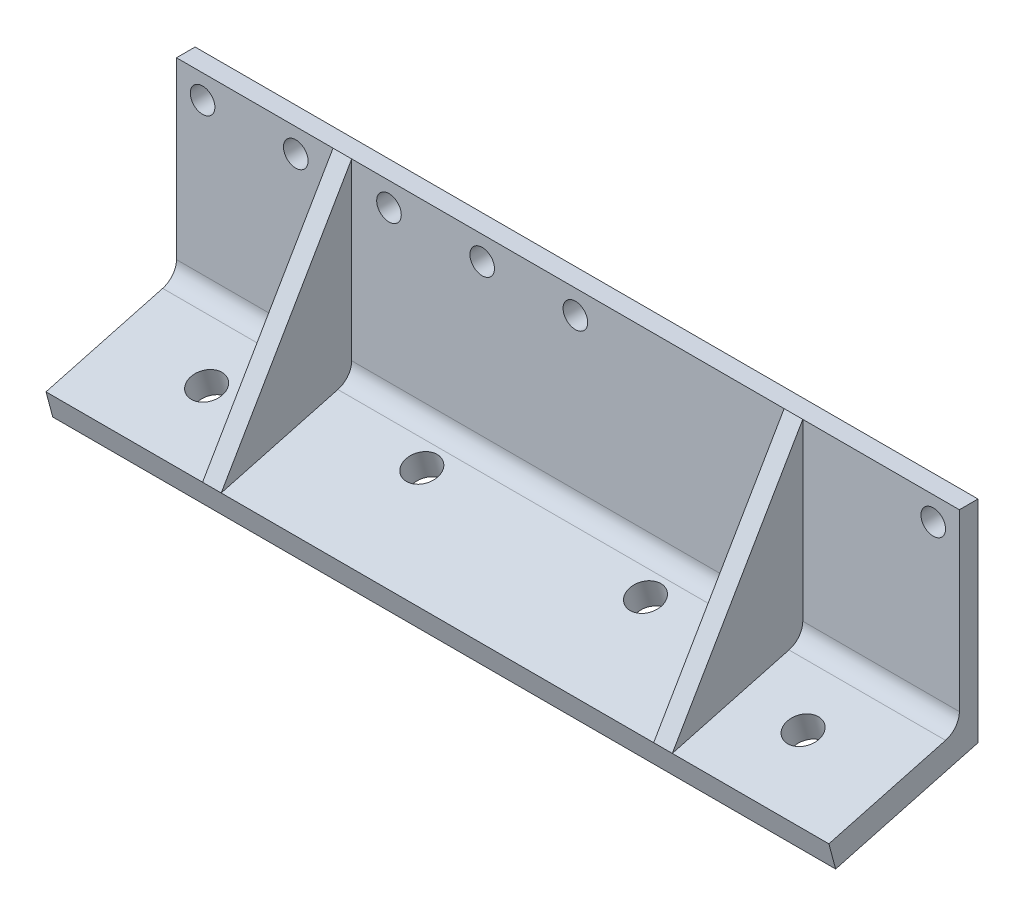
SolidWorks part; units mm, degrees
material "1060 合金"
ref_plane "前视基准面" through (0, 0, 0) normal (0, 0, 1) x (1, 0, 0)
ref_plane "上视基准面" through (0, 0, 0) normal (0, 1, 0) x (1, 0, 0)
ref_plane "右视基准面" through (0, 0, 0) normal (1, 0, 0) x (0, 0, -1)
sketch "草图1" plane through (0, 0, 0) normal (0, 1, 0) x (1, 0, 0)
  line L0 (0, 0) -> (170, 0) construction
  line L1 (170, 31.93) -> (170, -31.93)
  line L2 (15.8391, 73.3084) -> (162.1119, 41.7045)
  line L3 (15.8391, -73.3084) -> (162.1119, -41.7045)
  arc A0 (15.8391, 73.3084) -> (15.8391, -73.3084) centre (0, 0) ccw
  arc A1 (162.1119, -41.7045) -> (170, -31.93) centre (160, -31.93) ccw
  arc A2 (170, 31.93) -> (162.1119, 41.7045) centre (160, 31.93) ccw
  point P6 (170, 0)
  dimension "D1" = 150
  dimension "D4" = 20
  dimension "D5" = 20
  dimension "D2" = 170
  dimension "D3" = 63.86
extrude "凸台-拉伸1" add sketch "草图1" along normal blind 30
sketch "草图2" plane through (0, 30, 0) normal (0, 1, 0) x (1, 0, 0)
  circle A0 centre (0, 0) radius 44.45
  dimension "D1" = 88.9
extrude "切除-拉伸1" cut sketch "草图2" against normal blind 4
sketch "草图3" plane through (0, 26, 0) normal (0, 1, 0) x (1, 0, 0)
  line L0 (0, 0) -> (0, 90.3276) construction
  circle A0 centre (0, 0) radius 25.5
  circle A1 centre (0, 41) radius 2.25
  circle A2 centre (28.9914, 28.9914) radius 2.25
  circle A3 centre (41, 0) radius 2.25
  circle A4 centre (28.9914, -28.9914) radius 2.25
  circle A5 centre (0, -41) radius 2.25
  circle A6 centre (-28.9914, -28.9914) radius 2.25
  circle A7 centre (-41, 0) radius 2.25
  circle A8 centre (-28.9914, 28.9914) radius 2.25
  dimension "D1" = 51
  dimension "D3" = 4.5
  dimension "D2" = 41
  dimension "D4" = 8
extrude "切除-拉伸2" cut sketch "草图3" against normal through all contours A2 | A3 | A4 | A5 | A6 | A7 | A8 | A1 | A0
sketch "草图4" plane through (0, 30, 0) normal (0, 1, 0) x (1, 0, 0)
  line L0 (0, 0) -> (134, 0) construction
  line L1 (124, 18.5) -> (134, 18.5)
  line L2 (124, -18.5) -> (134, -18.5)
  arc A0 (134, -18.5) -> (134, 18.5) centre (134, 0) ccw
  arc A1 (124, 18.5) -> (124, -18.5) centre (124, 0) ccw
  dimension "D2" = 37
  dimension "D3" = 37
  dimension "D1" = 134
  dimension "D4" = 10
extrude "切除-拉伸3" cut sketch "草图4" against normal through all
sketch "草图5" plane through (0, 30, 0) normal (0, 1, 0) x (1, 0, 0)
  arc A0 (134, -18.5) -> (134, 18.5) centre (134, 0) ccw construction
  arc A1 (124, 18.5) -> (124, -18.5) centre (124, 0) ccw construction
  arc A2 (134, -18.5) -> (134, 18.5) centre (134, 0) ccw construction
  arc A3 (124, 18.5) -> (124, -18.5) centre (124, 0) ccw construction
  circle A4 centre (116.75, 25.5) radius 1.65
  circle A5 centre (141.25, 25.5) radius 1.65
  circle A6 centre (141.25, -25.5) radius 1.65
  circle A7 centre (116.75, -25.5) radius 1.65
  dimension "D1" = 3.3
  dimension "D2" = 3.3
  dimension "D3" = 3.3
  dimension "D4" = 3.3
  dimension "D7" = 25.5
  dimension "D5" = 7.25
  dimension "D6" = 25.5
  dimension "D8" = 7.25
  dimension "D9" = 7.25
extrude "切除-拉伸4" cut sketch "草图5" against normal through all
sketch "草图6" plane through (0, 30, 0) normal (0, 1, 0) x (1, 0, 0)
  line L0 (158, 42.5929) -> (158, -42.5929) construction
  line L2 (-52, 54.0463) -> (-52, -54.0463) construction
  line L6 (162.1119, 41.7045) -> (15.8391, 73.3084) construction
  line L7 (15.8391, -73.3084) -> (162.1119, -41.7045) construction
  line L8 (-52, 95) -> (-52, -95)
  line L9 (158, 95) -> (158, -95)
  line L10 (-52, 95) -> (158, 95)
  line L11 (-52, -95) -> (158, -95)
  line L15 (162.1119, 41.7045) -> (15.8391, 73.3084)
  line L16 (15.8391, -73.3084) -> (162.1119, -41.7045)
  line L17 (170, -31.93) -> (170, 31.93)
  line L18 (162.1119, 41.7045) -> (15.8391, 73.3084)
  line L19 (15.8391, -73.3084) -> (162.1119, -41.7045)
  line L20 (170, -31.93) -> (170, 31.93)
  arc A0 (15.8391, 73.3084) -> (15.8391, -73.3084) centre (0, 0) ccw construction
  arc A6 (170, 31.93) -> (162.1119, 41.7045) centre (160, 31.93) ccw
  arc A7 (15.8391, 73.3084) -> (15.8391, -73.3084) centre (0, 0) ccw
  arc A8 (162.1119, -41.7045) -> (170, -31.93) centre (160, -31.93) ccw
  arc A9 (170, 31.93) -> (162.1119, 41.7045) centre (160, 31.93) ccw
  arc A10 (15.8391, 73.3084) -> (15.8391, -73.3084) centre (0, 0) ccw
  arc A11 (162.1119, -41.7045) -> (170, -31.93) centre (160, -31.93) ccw
  point P8 (-52, 0)
  point P13 (158, 0)
  line M26 (162.1119, 41.7045) -> (15.8391, 73.3084)
  arc M27 (15.8391, 73.3084) -> (15.8391, -73.3084) centre (0, 0) ccw
  line M28 (15.8391, -73.3084) -> (162.1119, -41.7045)
  dimension "D3" = 190
  dimension "D1" = 210
  dimension "D2" = 52
  dimension "D4" = 190
  dimension "D5" = 0
extrude "凸台-拉伸2" add sketch "草图6" against normal blind 30 contours L10 L8 L9 M27 M26 | L8 L11 L9 M28 M27
sketch "草图7" plane through (0, 30, 0) normal (0, 1, 0) x (1, 0, 0)
  line L0 (-52, 54.0463) -> (-52, -54.0463)
  line L1 (158, 42.5929) -> (158, -42.5929)
  line L9 (162.1119, 41.7045) -> (158, 42.5929)
  line L10 (158, 42.5929) -> (158, 95)
  line L11 (158, 95) -> (-52, 95)
  line L12 (-52, 95) -> (-52, 54.0463)
  line L13 (-52, -54.0463) -> (-52, -95)
  line L14 (-52, -95) -> (158, -95)
  line L15 (158, -95) -> (158, -42.5929)
  line L16 (158, -42.5929) -> (162.1119, -41.7045)
  line L17 (170, -31.93) -> (170, 31.93)
  line L18 (162.1119, 41.7045) -> (158, 42.5929)
  line L21 (-52, 95) -> (-52, 54.0463)
  line L25 (158, -42.5929) -> (162.1119, -41.7045)
  line L26 (170, -31.93) -> (170, 31.93)
  arc A3 (170, 31.93) -> (162.1119, 41.7045) centre (160, 31.93) ccw
  arc A4 (-52, 54.0463) -> (-52, -54.0463) centre (0, 0) ccw
  arc A5 (162.1119, -41.7045) -> (170, -31.93) centre (160, -31.93) ccw
  arc A6 (170, 31.93) -> (162.1119, 41.7045) centre (160, 31.93) ccw
  arc A7 (-52, 54.0463) -> (-52, -54.0463) centre (0, 0) ccw
  arc A8 (162.1119, -41.7045) -> (170, -31.93) centre (160, -31.93) ccw
  arc M22 (170, 31.93) -> (162.1119, 41.7045) centre (160, 31.93) ccw
  line M23 (162.1119, 41.7045) -> (158, 42.5929)
  arc M27 (-52, 54.0463) -> (-52, -54.0463) centre (0, 0) ccw
  line M31 (158, -42.5929) -> (162.1119, -41.7045)
  arc M32 (162.1119, -41.7045) -> (170, -31.93) centre (160, -31.93) ccw
  line M33 (170, -31.93) -> (170, 31.93)
  dimension "D1" = 0
extrude "切除-拉伸5" cut sketch "草图7" against normal through all contours L0 M27 | L1 M23 M31 M32 M33 M22
sketch "草图9" plane through (-52, 0, 0) normal (-1, 0, 0) x (0, 0, 1)
  line L0 (-95, 20) -> (-60, 10.6218)
  line L1 (-95, 30) -> (95, 30) construction
  line L3 (-60, 10.6218) -> (-60, 30)
  line L5 (-95, 0) -> (-95, 30) construction
  line L7 (-95, 20) -> (-95, 30)
  line L8 (-95, 30) -> (-60, 30)
  dimension "D1" = 15
  dimension "D3" = 19.3782
  dimension "D4" = 35
  dimension "D5" = 10
extrude "切除-拉伸7" cut sketch "草图9" against normal through all contours L8 L3 L0 L7
sketch "草图8" plane through (-52, 0, 0) normal (-1, 0, 0) x (0, 0, 1)
  line L0 (0, 0) -> (52, 0)
  line L1 (-95, 0) -> (95, 0) construction
  line L2 (52, 0) -> (52, 17.3)
  line L3 (52, 17.3) -> (-52, 17.3)
  line L4 (-52, 17.3) -> (-52, 0)
  line L5 (-52, 0) -> (0, 0)
  line L6 (-60, 30) -> (95, 30) construction
  dimension "D1" = 52
  dimension "D2" = 52
  dimension "D3" = 12.7
sketch "草图10" plane through (-52, 0, 0) normal (-1, 0, 0) x (0, 0, 1)
  line L0 (-95, 12.7531) -> (-47.4049, 0) construction
  line L1 (-95, 0) -> (-95, 20) construction
  line L2 (-95, 0) -> (95, 0) construction
  line L3 (-95, 20) -> (-60, 10.6218) construction
  line L6 (-95, 12.7531) -> (-52, 1.2313)
  line L7 (-52, 1.2313) -> (-52, 0)
  line L8 (-95, 12.7531) -> (-95, 0)
  line L9 (-95, 0) -> (-52, 0)
  line L10 (-52, 17.3) -> (-52, 0) construction
  dimension "D1" = 7
extrude "切除-拉伸8" cut sketch "草图10" against normal through all
extrude "切除-拉伸9" cut sketch "草图8" against normal through all
fillet "圆角1" radius 5 1 edges at (53, 10.6218, -60)
sketch "草图11" plane through (-52, 0, 0) normal (-1, 0, 0) x (0, 0, 1)
  line L0 (-95, 12.7531) -> (-93.1883, 19.5145)
  line L1 (-95, 20) -> (-66.2941, 12.3083) construction
  line L2 (-93.1883, 19.5145) -> (-95, 20)
  line L3 (-95, 20) -> (-95, 12.7531)
extrude "切除-拉伸10" cut sketch "草图11" against normal through all
sketch "草图12" plane through (-52, 0, 0) normal (-1, 0, 0) x (0, 0, 1)
  line L0 (-93.1883, 19.5145) -> (-60, 30)
  line L10 (-93.1883, 19.5145) -> (-95, 12.7531)
  line L11 (-95, 12.7531) -> (-52, 1.2313)
  line L12 (-52, 1.2313) -> (-52, 17.3)
  line L13 (-52, 17.3) -> (52, 17.3)
  line L14 (52, 17.3) -> (52, 0)
  line L15 (52, 0) -> (95, 0)
  line L16 (95, 0) -> (95, 30)
  line L17 (95, 30) -> (-60, 30)
  line L18 (-60, 30) -> (-60, 17.1379)
  line L19 (-66.2941, 12.3083) -> (-93.1883, 19.5145)
  line L28 (-60, 30) -> (-60, 17.1379)
  line L29 (-66.2941, 12.3083) -> (-93.1883, 19.5145)
  arc A1 (-66.2941, 12.3083) -> (-60, 17.1379) centre (-65, 17.1379) ccw
  arc A2 (-66.2941, 12.3083) -> (-60, 17.1379) centre (-65, 17.1379) ccw
  dimension "D1" = 0
extrude "凸台-拉伸3" add sketch "草图12" against normal blind 5
sketch "草图13" plane through (158, 0, 0) normal (1, 0, 0) x (0, 0, -1)
  line L3 (66.2941, 12.3083) -> (93.1883, 19.5145)
  line L4 (93.1883, 19.5145) -> (60, 30)
  line L5 (60, 30) -> (60, 17.1379)
  line L6 (66.2941, 12.3083) -> (93.1883, 19.5145)
  line L7 (93.1883, 19.5145) -> (60, 30)
  line L8 (60, 30) -> (60, 17.1379)
  arc A1 (60, 17.1379) -> (66.2941, 12.3083) centre (65, 17.1379) ccw
  arc A2 (60, 17.1379) -> (66.2941, 12.3083) centre (65, 17.1379) ccw
  dimension "D1" = 0
extrude "凸台-拉伸4" add sketch "草图13" against normal blind 5
sketch "草图14" plane through (0, -5.0897, -1.3638) normal (0, 0.9659, 0.2588) x (1, 0, 0)
  line L0 (153, 67.2208) -> (153, 95.0637) construction
  line L3 (153, 95.0637) -> (-47, 95.0637) construction
  circle A0 centre (-27, 82.0637) radius 4.25
  circle A1 centre (23, 82.0637) radius 4.25
  circle A2 centre (83, 82.0637) radius 4.25
  circle A3 centre (133, 82.0637) radius 4.25
  dimension "D1" = 8.5
  dimension "D2" = 160
  dimension "D3" = 20
  dimension "D4" = 50
  dimension "D5" = 50
  dimension "D6" = 13
extrude "切除-拉伸11" cut sketch "草图14" against normal through all
sketch "草图16" plane through (-52, 0, 0) normal (-1, 0, 0) x (0, 0, 1)
  line L0 (-60, 30) -> (95, 30) construction
  line L1 (95, 0) -> (52, 0)
  line L2 (95, 0) -> (95, 30)
  line L3 (95, 30) -> (52, 30)
  line L4 (52, 0) -> (52, 30)
extrude "切除-拉伸12" cut sketch "草图16" against normal through all
ref_plane "基准面1" through (0, -11.8512, -3.1755) normal (0, -0.9659, -0.2588) x (-1, 0, 0)
sketch "草图18" plane through (0, 30, 0) normal (0, 1, 0) x (1, 0, 0)
  line L1 (-52, -52) -> (158, -52)
  line L2 (-52, -52) -> (-52, -57)
  line L3 (-52, -57) -> (158, -57)
  line L4 (158, -52) -> (158, -57)
  dimension "D1" = 5
extrude "凸台-拉伸7" add sketch "草图18" against normal up to surface (56.6355 mm away) up to plane "基准面1"
sketch "草图19" plane through (-52, 0, 0) normal (-1, 0, 0) x (0, 0, 1)
  line L0 (57, -27.9752) -> (90.1883, -36.868)
  line L1 (90.1883, -36.868) -> (92, -30.1065)
  line L2 (92, -30.1065) -> (57, -20.7283)
  line L3 (57, -27.9752) -> (57, 30) construction
  line L4 (57, -20.7283) -> (57, -27.9752)
  line L5 (52, -26.6355) -> (57, -27.9752) construction
  dimension "D1" = 7
  dimension "D2" = 40
extrude "凸台-拉伸8" add sketch "草图19" against normal up to surface (210 mm away) up to face at (158, 8.1654, -14.9098)
sketch "草图20" plane through (-52, 0, 0) normal (-1, 0, 0) x (0, 0, 1)
  line L0 (92, -30.1065) -> (57, -20.7283) construction
  line L1 (57, -20.7283) -> (57, 30) construction
  line L2 (92, -30.1065) -> (57, -20.7283)
  line L3 (57, -20.7283) -> (57, 30)
  line L4 (57, 30) -> (92, -30.1065)
extrude "凸台-拉伸9" add sketch "草图20" against normal blind 5
sketch "草图21" plane through (158, 0, 0) normal (1, 0, 0) x (0, 0, -1)
  line L3 (-57, 30) -> (-92, -30.1065)
  line L4 (-92, -30.1065) -> (-57, -20.7283)
  line L5 (-57, -20.7283) -> (-57, 30)
  line L6 (-57, 30) -> (-92, -30.1065)
  line L7 (-92, -30.1065) -> (-57, -20.7283)
  line L8 (-57, -20.7283) -> (-57, 30)
  dimension "D1" = 0
extrude "凸台-拉伸10" add sketch "草图21" against normal blind 5
sketch "草图22" plane through (0, -5.0897, -1.3638) normal (0, 0.9659, 0.2588) x (1, 0, 0)
  line L0 (-47, -96.6573) -> (-47, -47.2932) construction
  line L2 (153, -96.6573) -> (153, -60.4226) construction
  circle A0 centre (-27, -77.9363) radius 4.25
  circle A1 centre (23, -69.9363) radius 4.25
  circle A2 centre (83, -69.9363) radius 4.25
  circle A3 centre (133, -77.9363) radius 4.25
  circle A4 centre (133, 82.0637) radius 4.25 construction
  circle A5 centre (-27, 82.0637) radius 4.25 construction
  circle A6 centre (23, 82.0637) radius 4.25 construction
  circle A7 centre (83, 82.0637) radius 4.25 construction
  dimension "D1" = 8.5
  dimension "D7" = 152
  dimension "D6" = 152
  dimension "D8" = 50
  dimension "D4" = 160
  dimension "D5" = 160
  dimension "D2" = 20
  dimension "D3" = 20
  dimension "D9" = 50
extrude "切除-拉伸13" cut sketch "草图22" against normal through all
fillet "圆角2" radius 5 1 edges at (53, -20.7283, 57)
sketch "草图23" plane through (-52, 0, 0) normal (-1, 0, 0) x (0, 0, 1)
  line L0 (52, -26.6355) -> (52, 17.3) construction
  line L1 (52, 56.9656) -> (-106.5122, 56.9656)
  line L2 (52, 56.9656) -> (52, -46.3521)
  line L3 (52, -46.3521) -> (-106.5122, -46.3521)
  line L4 (-106.5122, 56.9656) -> (-106.5122, -46.3521)
  point P6 (52, 56.9656)
  point P7 (52, -46.3521)
extrude "切除-拉伸14" cut sketch "草图23" against normal through all
sketch "草图24" plane through (0, 0, 57) normal (0, 0, 1) x (1, 0, 0)
  line L0 (-47, 30) -> (153, 30) construction
  circle A0 centre (-45, 23.65) radius 3.3
  circle A1 centre (151, 23.65) radius 3.3
  circle A2 centre (55, 23.65) radius 3.3
  circle A3 centre (30, 23.65) radius 3.3
  circle A4 centre (5, 23.65) radius 3.3
  circle A5 centre (-20, 23.65) radius 3.3
  point P12 (0, 0)
  dimension "D1" = 6.6
  dimension "D2" = 6.35
  dimension "D3" = 7
  dimension "D4" = 7
  dimension "D5" = 25
  dimension "D6" = 25
  dimension "D7" = 25
  dimension "D8" = 25
ref_plane "基准面2" through (-7.5, 0, 0) normal (-1, 0, 0) x (0, 0, 1)
ref_plane "基准面3" through (113.5, 0, 0) normal (1, 0, 0) x (0, 0, -1)
sketch "草图25" plane through (-7.5, 0, 0) normal (-1, 0, 0) x (0, 0, 1)
  line L3 (60.7059, -21.7213) -> (92, -30.1065)
  line L4 (57, 30) -> (57, -16.8916)
  line L5 (92, -30.1065) -> (57, 30)
  line L6 (60.7059, -21.7213) -> (92, -30.1065)
  line L7 (57, 30) -> (57, -16.8916)
  line L8 (92, -30.1065) -> (57, 30)
  arc A1 (57, -16.8916) -> (60.7059, -21.7213) centre (62, -16.8916) ccw
  arc A2 (57, -16.8916) -> (60.7059, -21.7213) centre (62, -16.8916) ccw
  dimension "D1" = 0
extrude "凸台-拉伸11" add sketch "草图25" along normal mid plane 5
sketch "草图26" plane through (113.5, 0, 0) normal (1, 0, 0) x (0, 0, -1)
  line L3 (-57, -16.8916) -> (-57, 30)
  line L4 (-92, -30.1065) -> (-60.7059, -21.7213)
  line L5 (-57, 30) -> (-92, -30.1065)
  line L6 (-57, -16.8916) -> (-57, 30)
  line L7 (-92, -30.1065) -> (-60.7059, -21.7213)
  line L8 (-57, 30) -> (-92, -30.1065)
  arc A1 (-60.7059, -21.7213) -> (-57, -16.8916) centre (-62, -16.8916) ccw
  arc A2 (-60.7059, -21.7213) -> (-57, -16.8916) centre (-62, -16.8916) ccw
  dimension "D1" = 0
extrude "凸台-拉伸12" add sketch "草图26" along normal mid plane 5
sketch "草图27" plane through (-47, 0, 0) normal (1, 0, 0) x (0, 0, -1)
  line L3 (-92, -30.1065) -> (-60.7059, -21.7213)
  line L4 (-57, -16.8916) -> (-57, 30)
  line L5 (-57, 30) -> (-92, -30.1065)
  line L6 (-92, -30.1065) -> (-60.7059, -21.7213)
  line L7 (-57, -16.8916) -> (-57, 30)
  line L8 (-57, 30) -> (-92, -30.1065)
  arc A1 (-60.7059, -21.7213) -> (-57, -16.8916) centre (-62, -16.8916) ccw
  arc A2 (-60.7059, -21.7213) -> (-57, -16.8916) centre (-62, -16.8916) ccw
  dimension "D1" = 0
extrude "切除-拉伸15" cut sketch "草图27" against normal blind 5
sketch "草图28" plane through (153, 0, 0) normal (-1, 0, 0) x (0, 0, 1)
  line L3 (57, 30) -> (57, -16.8916)
  line L4 (60.7059, -21.7213) -> (92, -30.1065)
  line L5 (92, -30.1065) -> (57, 30)
  line L6 (57, 30) -> (57, -16.8916)
  line L7 (60.7059, -21.7213) -> (92, -30.1065)
  line L8 (92, -30.1065) -> (57, 30)
  arc A1 (57, -16.8916) -> (60.7059, -21.7213) centre (62, -16.8916) ccw
  arc A2 (57, -16.8916) -> (60.7059, -21.7213) centre (62, -16.8916) ccw
  dimension "D1" = 0
extrude "切除-拉伸16" cut sketch "草图28" against normal blind 5
extrude "切除-拉伸17" cut sketch "草图24" against normal through all
